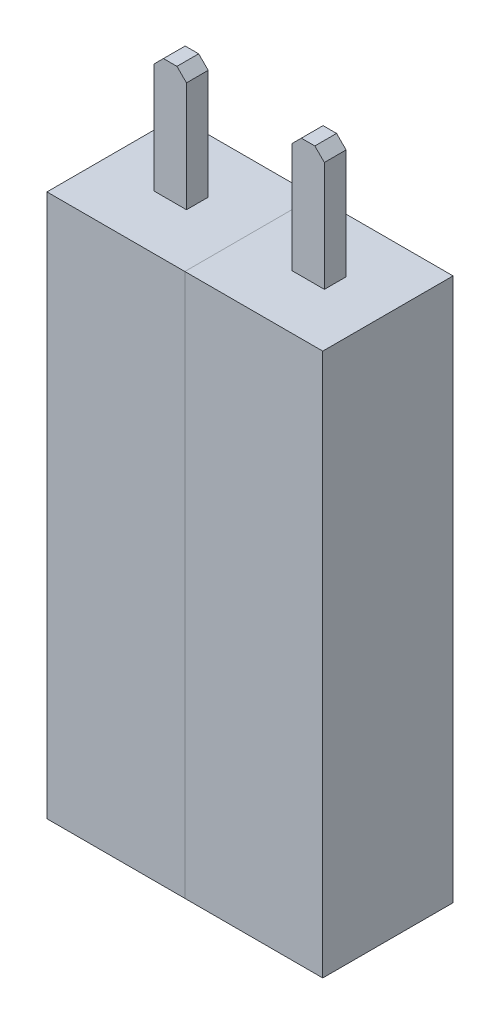
SolidWorks part; units mm, degrees
ref_plane "Front Plane" through (0, 0, 0) normal (0, 0, 1) x (1, 0, 0)
ref_plane "Top Plane" through (0, 0, 0) normal (0, 1, 0) x (1, 0, 0)
ref_plane "Right Plane" through (0, 0, 0) normal (1, 0, 0) x (0, 0, -1)
sketch "Sketch1" plane through (0, 0, 0) normal (0, 0, 1) x (1, 0, 0)
  line L1 (-1.27, 5) -> (1.27, 5)
  line L2 (-1.27, 5) -> (-1.27, -5)
  line L3 (-1.27, -5) -> (1.27, -5)
  line L4 (1.27, 5) -> (1.27, -5)
  line L5 (-1.27, 5) -> (1.27, -5) construction
  line L6 (-1.27, -5) -> (1.27, 5) construction
  point P0 (0, 0)
  dimension "D1" = 2.54
  dimension "D2" = 10
extrude "Boss-Extrude1" add sketch "Sketch1" along normal mid plane 2.4
sketch "Sketch2" plane through (0, -5, 0) normal (0, -1, 0) x (1, 0, 0)
  line L0 (0, -1.2) -> (0, 1.2) construction
  line L1 (-1.27, 1.2) -> (1.27, 1.2) construction
  line L2 (-1.27, -1.2) -> (1.27, -1.2) construction
  line L4 (-0.6, 0.6) -> (0.6, 0.6)
  line L5 (-0.6, 0.6) -> (-0.6, -0.6)
  line L6 (-0.6, -0.6) -> (0.6, -0.6)
  line L7 (0.6, 0.6) -> (0.6, -0.6)
  line L8 (-0.6, 0.6) -> (0.6, -0.6) construction
  line L9 (-0.6, -0.6) -> (0.6, 0.6) construction
  point P5 (0, 0)
  dimension "D1" = 1.2
extrude "Cut-Extrude1" cut sketch "Sketch2" against normal blind 7
sketch "Sketch3" plane through (0, 0, 0) normal (0, 0, 1) x (1, 0, 0)
  line L0 (-0.3, 5) -> (-0.3, 7.0243)
  line L1 (1.27, 5) -> (-1.27, 5) construction
  line L2 (-0.3, 7.0243) -> (-0.1243, 7.2)
  line L3 (-0.1243, 7.2) -> (0.1243, 7.2)
  line L4 (0, 7.2) -> (0, 5) construction
  line L5 (-0.3, 5) -> (0.3, 5)
  line L6 (0.3, 7.0243) -> (0.1243, 7.2)
  line L7 (0.3, 5) -> (0.3, 7.0243)
  dimension "D1" = 0.6
  dimension "D2" = 45
  dimension "D3" = 2.2
extrude "Boss-Extrude2" add sketch "Sketch3" along normal mid plane 0.4
pattern_linear "LPattern1" count 2 spacing 2.54 along (1, 0, 0) of bodies 103
